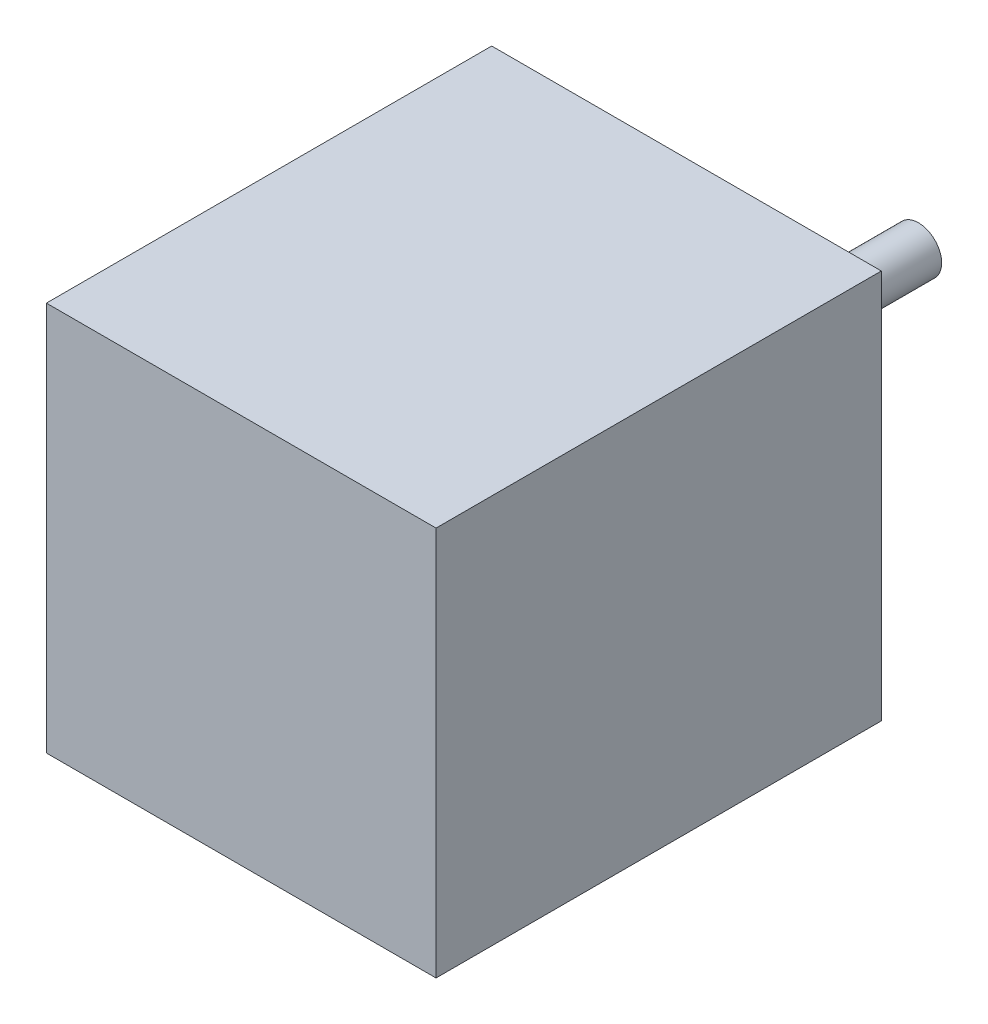
SolidWorks part; units mm, degrees
other "标注1"
sketch "草图7" plane through (-42, 0, -24) normal (-1, 0, 0) x (0, 0, 1)
sketch "草图8" plane through (-42, 0, -24) normal (-1, 0, 0) x (0, 0, 1)
sketch "草图9" plane through (-42, 0, -20) normal (-1, 0, 0) x (0, 0, 1)
sketch "草图10" plane through (-42, 0, -20) normal (-1, 0, 0) x (0, 0, 1)
sketch "草图11" plane through (-42, 0, -20) normal (-1, 0, 0) x (0, 0, 1)
ref_plane "前视基准面" through (0, 0, 0) normal (0, 0, 1) x (1, 0, 0)
ref_plane "上视基准面" through (0, 0, 0) normal (0, 1, 0) x (1, 0, 0)
ref_plane "右视基准面" through (0, 0, 0) normal (1, 0, 0) x (0, 0, -1)
sketch "草图1" plane through (0, 0, 0) normal (0, 0, 1) x (1, 0, 0)
  line L1 (0, 0) -> (-42, 0)
  line L2 (0, 0) -> (0, 42)
  line L3 (0, 42) -> (-42, 42)
  line L4 (-42, 0) -> (-42, 42)
  dimension "D1" = 42
  dimension "D2" = 42
extrude "凸台-拉伸1" add sketch "草图1" along normal blind 48
sketch "草图3" plane through (0, 0, 0) normal (0, 0, -1) x (-1, 0, 0)
  line L0 (0, 42) -> (42, 42) construction
  line L1 (0, 0) -> (0, 42) construction
  circle A0 centre (21, 21) radius 11
  dimension "D3" = 22
  dimension "D1" = 21
  dimension "D2" = 21
extrude "凸台-拉伸2" add sketch "草图3" along normal blind 2
sketch "草图4" plane through (0, 0, -2) normal (0, 0, -1) x (-1, 0, 0)
  circle A0 centre (21, 21) radius 2.5
  dimension "D1" = 5
extrude "凸台-拉伸3" add sketch "草图4" along normal blind 23
sketch "草图5" plane through (0, 0, 0) normal (0, 0, -1) x (-1, 0, 0)
  line L0 (0, 0) -> (5.5, 0) construction
  line L1 (42, 0) -> (0, 0) construction
  line L2 (5.5, 0) -> (5.5, 5.5) construction
  line L3 (5.5, 5.5) -> (36.5, 5.5) construction
  line L4 (36.5, 5.5) -> (36.5, 36.5) construction
  line L5 (36.5, 36.5) -> (5.5, 36.5) construction
  circle A0 centre (5.5, 5.5) radius 1.5
  circle A1 centre (36.5, 5.5) radius 1.5
  circle A2 centre (36.5, 36.5) radius 1.5
  circle A3 centre (5.5, 36.5) radius 1.5
  dimension "D6" = 3
  dimension "D7" = 3
  dimension "D8" = 3
  dimension "D9" = 3
  dimension "D1" = 5.5
  dimension "D2" = 5.5
  dimension "D3" = 31
  dimension "D4" = 31
  dimension "D5" = 31
extrude "切除-拉伸1" cut sketch "草图5" against normal blind 8
sketch "草图6" plane through (0, 0, 48) normal (0, 0, 1) x (1, 0, 0)
  circle A0 centre (-21, 21) radius 2.5
  dimension "D1" = 5
